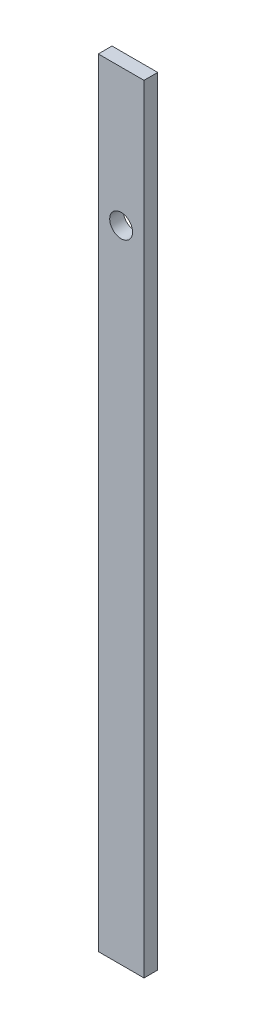
SolidWorks part; units mm, degrees
ref_plane "前基準面" through (0, 0, 0) normal (0, 0, 1) x (1, 0, 0)
ref_plane "上基準面" through (0, 0, 0) normal (0, 1, 0) x (1, 0, 0)
ref_plane "右基準面" through (0, 0, 0) normal (1, 0, 0) x (0, 0, -1)
sketch "草圖1" plane through (0, 0, 0) normal (0, 0, 1) x (1, 0, 0)
  line L1 (-5, -85) -> (5, -85)
  line L2 (-5, -85) -> (-5, 85)
  line L3 (-5, 85) -> (5, 85)
  line L4 (5, -85) -> (5, 85)
  line L5 (-5, -85) -> (5, 85) construction
  line L6 (-5, 85) -> (5, -85) construction
  circle A0 centre (0, 55) radius 2.5
  point P0 (0, 0)
  point P8 (0, 0)
  point P9 (0, 85)
  dimension "D3" = 5
  dimension "D1" = 10
  dimension "D2" = 170
  dimension "D4" = 30
extrude "填料-伸長1" add sketch "草圖1" along normal blind 3
